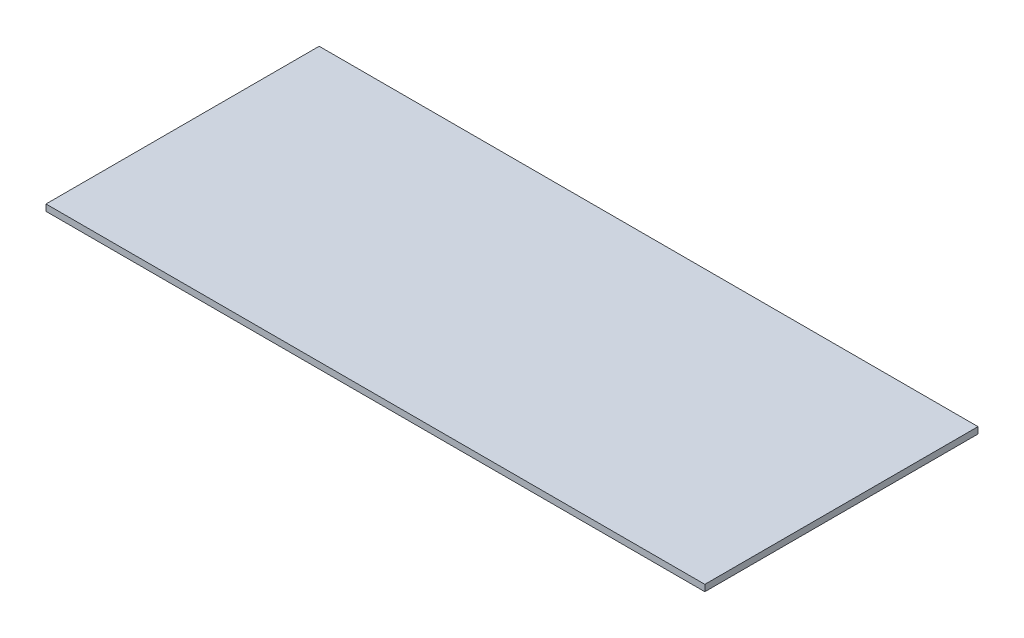
SolidWorks part; units mm, degrees
ref_plane "Front Plane" through (0, 0, 0) normal (0, 0, 1) x (1, 0, 0)
ref_plane "Top Plane" through (0, 0, 0) normal (0, 1, 0) x (1, 0, 0)
ref_plane "Right Plane" through (0, 0, 0) normal (1, 0, 0) x (0, 0, -1)
sketch "Sketch1" plane through (0, 0, 0) normal (0, 1, 0) x (1, 0, 0)
  line L1 (-205, 85) -> (205, 85)
  line L2 (-205, 85) -> (-205, -85)
  line L3 (-205, -85) -> (205, -85)
  line L4 (205, 85) -> (205, -85)
  line L5 (-205, 85) -> (205, -85) construction
  line L6 (-205, -85) -> (205, 85) construction
  point P0 (0, 0)
  dimension "D1" = 410
  dimension "D2" = 170
extrude "Boss-Extrude1" add sketch "Sketch1" along normal blind 4
